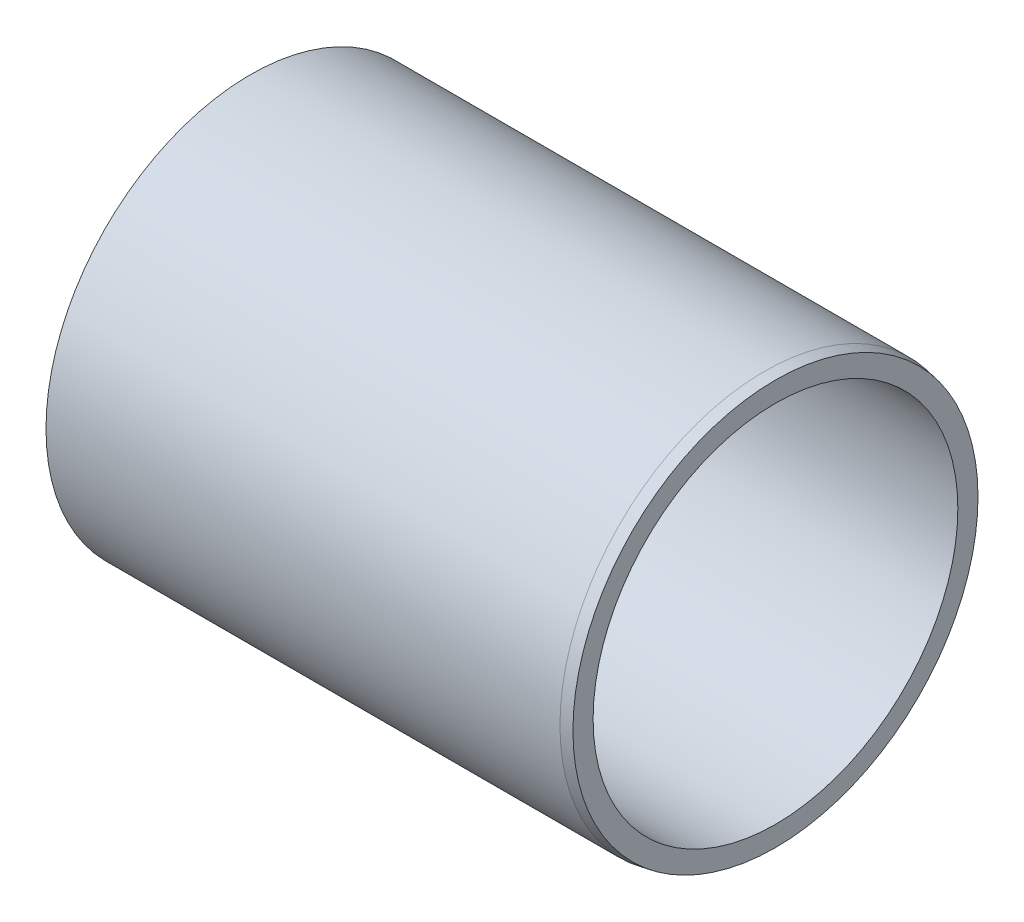
SolidWorks part; units mm, degrees
material "Алюминиевая бронза"
ref_plane "Спереди" through (0, 0, 0) normal (0, 0, 1) x (1, 0, 0)
ref_plane "Сверху" through (0, 0, 0) normal (0, 1, 0) x (1, 0, 0)
ref_plane "Справа" through (0, 0, 0) normal (1, 0, 0) x (0, 0, -1)
sketch "Эскиз1" plane through (0, 0, 0) normal (0, 0, 1) x (1, 0, 0)
  line L0 (0, 0) -> (87.5057, 0) construction
  line L1 (93, 37) -> (95, 36.6473)
  line L2 (0, 33) -> (95, 33)
  line L3 (0, 33) -> (0, 37)
  line L4 (0, 37) -> (93, 37)
  line L5 (95, 33) -> (95, 36.6473)
  point P4 (95, 37)
  dimension "D1" = 95
  dimension "D2" = 4
  dimension "D3" = 66
  dimension "D4" = 2
  dimension "D5" = 10
revolve "Повернуть1" add sketch "Эскиз1" angle 360 about L0
